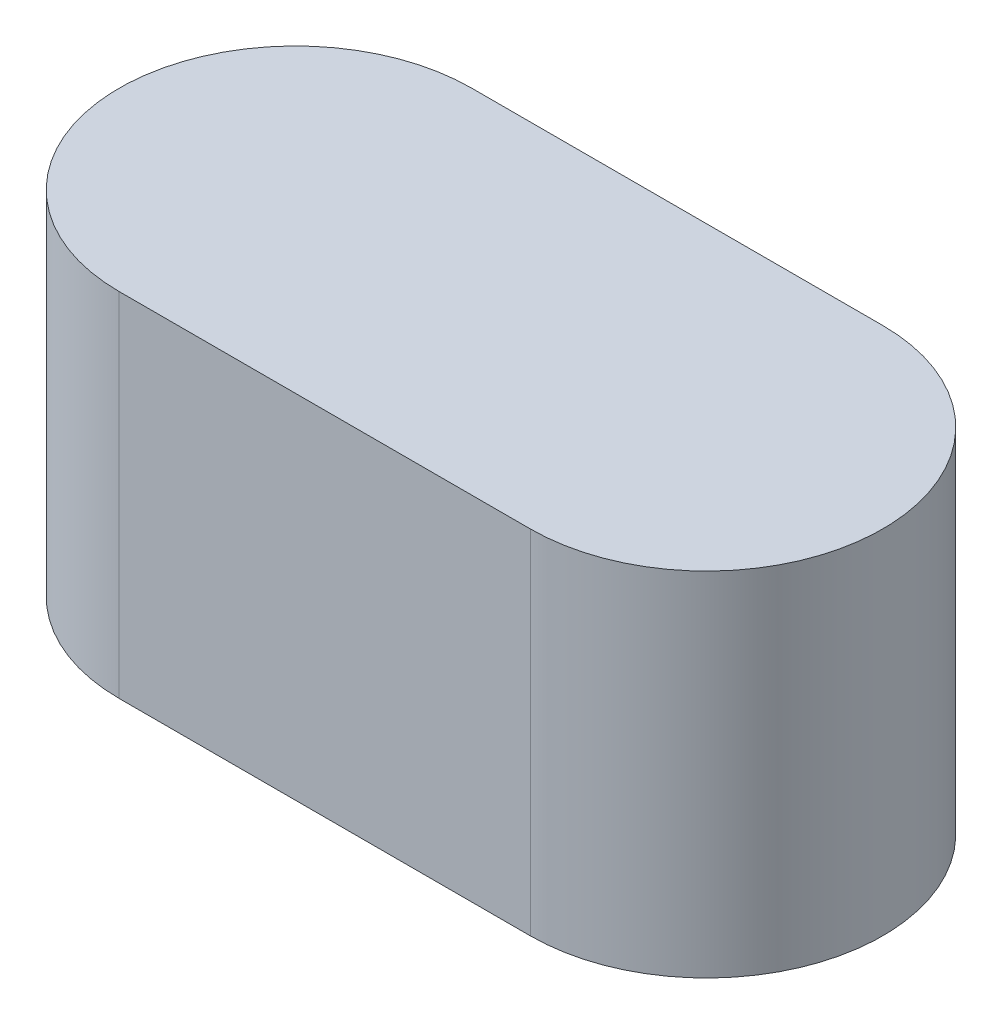
SolidWorks part; units mm, degrees
ref_plane "Front Plane" through (0, 0, 0) normal (0, 0, 1) x (1, 0, 0)
ref_plane "Top Plane" through (0, 0, 0) normal (0, 1, 0) x (1, 0, 0)
ref_plane "Right Plane" through (0, 0, 0) normal (1, 0, 0) x (0, 0, -1)
sketch "Sketch1" plane through (0, 0, 0) normal (0, 1, 0) x (1, 0, 0)
  line L1 (-3.5, -3) -> (3.5, -3)
  line L3 (-3.5, 3) -> (3.5, 3)
  arc A1 (3.5, -3) -> (3.5, 3) centre (3.5, 0) ccw
  arc A3 (-3.5, 3) -> (-3.5, -3) centre (-3.5, 0) ccw
  point P0 (0, 0)
extrude "Boss-Extrude1" add sketch "Sketch1" along normal blind 6
